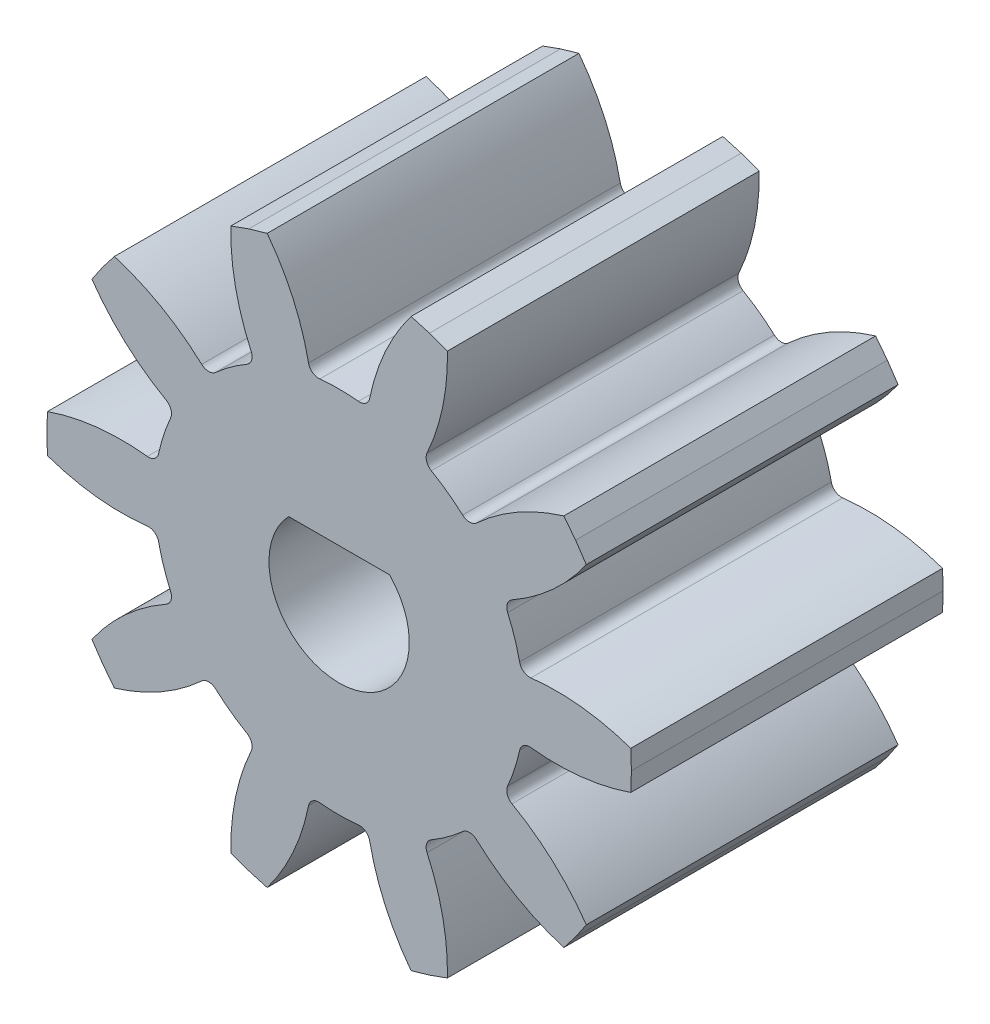
SolidWorks part; units mm, degrees
ref_plane "Front Plane" through (0, 0, 0) normal (0, 0, 1) x (1, 0, 0)
ref_plane "Top Plane" through (0, 0, 0) normal (0, 1, 0) x (1, 0, 0)
ref_plane "Right Plane" through (0, 0, 0) normal (1, 0, 0) x (0, 0, -1)
sketch "Sketch1" plane through (0, 0, 0) normal (0, 0, 1) x (1, 0, 0)
  line L0 (0, 0) -> (74.4139, 0) construction
  line L1 (0, 0) -> (5.6279, 1.8286) construction
  line L2 (0, 0) -> (74.4139, 11.786) construction
  line L3 (0, 0) -> (74.4139, 4.8773) construction
  line L4 (9.3549, 0.6132) -> (9.375, 0)
  line L5 (0, 0) -> (5.6279, -1.8286) construction
  line L6 (0, 0) -> (5.6279, 1.8286)
  line L7 (0, 0) -> (5.6279, -1.8286) construction
  line L8 (0, 0) -> (5.6279, -1.8286)
  line L9 (9.3549, -0.6132) -> (9.375, 0)
  circle A0 centre (0, 0) radius 9.375 construction
  circle A1 centre (0, 0) radius 7.8125 construction
  circle A2 centre (0, 0) radius 5.9175 construction
  arc A3 (5.8446, 0.9257) -> (9.3549, 0.6132) centre (6.9771, -6.2243) cw
  arc A4 (5.8446, 0.9257) -> (5.6279, 1.8286) centre (0, 0) ccw
  arc A5 (5.8446, -0.9257) -> (5.6279, -1.8286) centre (0, 0) cw
  arc A6 (5.8446, -0.9257) -> (9.3549, -0.6132) centre (6.9771, 6.2243) ccw
  dimension "D1" = 18.75
  dimension "D2" = 1.5625
  dimension "D3" = 1.895
  dimension "D4" = 18
  dimension "D5" = 9
  dimension "D6" = 3.75
extrude "Boss-Extrude1" add sketch "Sketch1" along normal blind 10
fillet "Fillet1" radius 0.3325 2 edges at (5.8446, 0.9257, 5) (5.8446, -0.9257, 5)
pattern_circular "CirPattern1" count 10 over 360 about axis through (0, 0, 0) along (0, 0, 1) of "Boss-Extrude1", "Fillet1"
sketch "Sketch2" plane through (0, 0, 0) normal (0, 0, -1) x (-1, 0, 0)
  line L0 (-1.6166, 1.565) -> (1.6166, 1.565)
  arc A0 (-1.6166, 1.565) -> (1.6166, 1.565) centre (0, 0) ccw
  dimension "D1" = 4.5
  dimension "D2" = 1.565
extrude "Cut-Extrude1" cut sketch "Sketch2" against normal up to next
